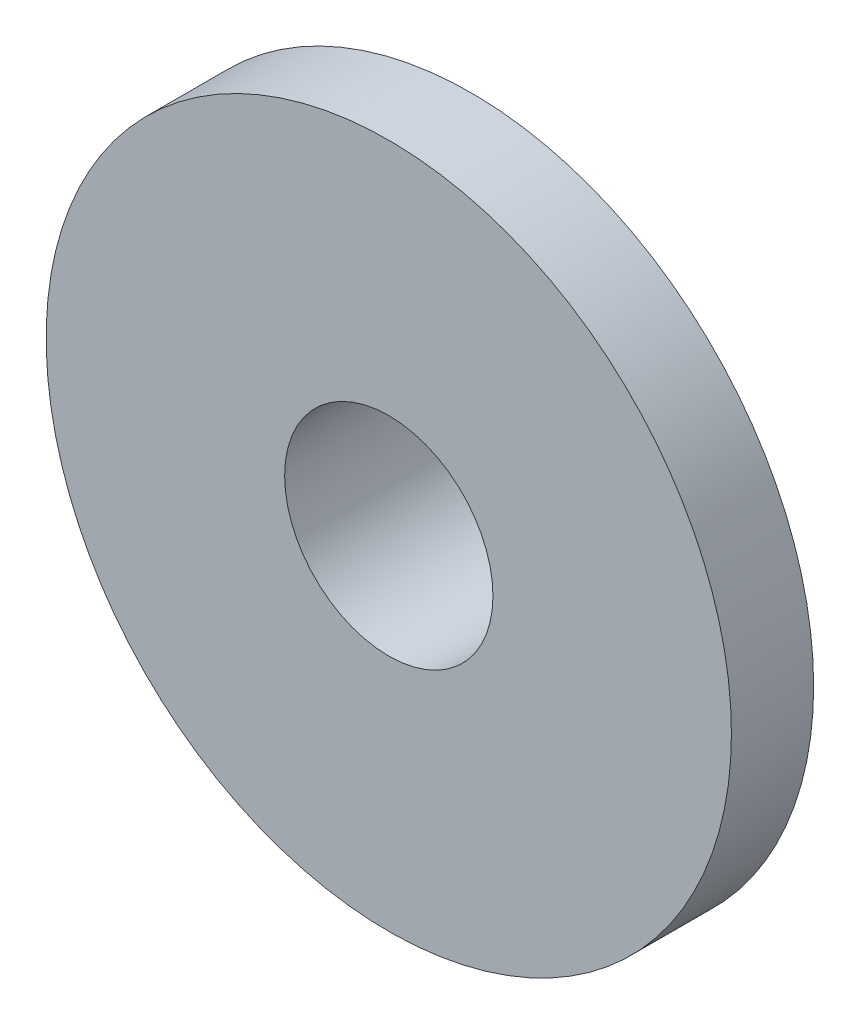
SolidWorks part; units mm, degrees
ref_plane "Front" through (0, 0, 0) normal (0, 0, 1) x (1, 0, 0)
ref_plane "Top" through (0, 0, 0) normal (0, 1, 0) x (1, 0, 0)
ref_plane "Right" through (0, 0, 0) normal (1, 0, 0) x (0, 0, -1)
sketch "Esquisse1" plane through (0, 0, 0) normal (0, 0, 1) x (1, 0, 0)
  circle A0 centre (0, 0) radius 11.5
extrude "Boss.-Extru.1" add sketch "Esquisse1" along normal blind 13
sketch "Esquisse2" plane through (0, 0, 13) normal (0, 0, 1) x (1, 0, 0)
  circle A0 centre (0, 0) radius 25
  circle A1 centre (0, 0) radius 7.5
  dimension "D1" = 50
extrude "Boss.-Extru.2" add sketch "Esquisse2" against normal blind 6
sketch "Esquisse5" plane through (0, 0, 13) normal (0, 0, 1) x (1, 0, 0)
  circle A0 centre (0, 0) radius 7.6
  dimension "D1" = 15.2
extrude "Enlèv. mat.-Extru.1" cut sketch "Esquisse5" against normal through all
